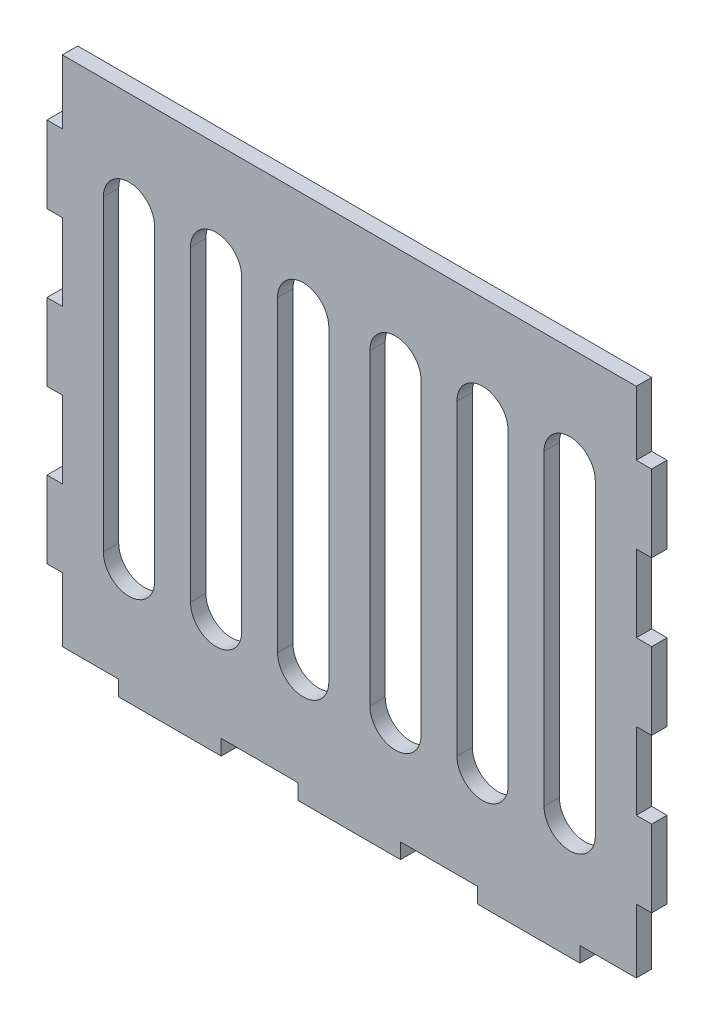
SolidWorks part; units mm, degrees
ref_plane "Front Plane" through (0, 0, 0) normal (0, 0, 1) x (1, 0, 0)
ref_plane "Top Plane" through (0, 0, 0) normal (0, 1, 0) x (1, 0, 0)
ref_plane "Right Plane" through (0, 0, 0) normal (1, 0, 0) x (0, 0, -1)
sketch "Sketch1" plane through (0, 0, 0) normal (0, 0, 1) x (1, 0, 0)
  line L0 (-43, -30) -> (-43, 30) construction
  line L1 (56, -50) -> (-56, -50)
  line L2 (56, -50) -> (56, 50)
  line L3 (56, 50) -> (-56, 50)
  line L4 (-56, -50) -> (-56, 50)
  line L5 (56, -50) -> (-56, 50) construction
  line L6 (56, 50) -> (-56, -50) construction
  line L7 (-48, -30) -> (-48, 30)
  line L8 (-38, -30) -> (-38, 30)
  line L9 (-26, -30) -> (-26, 30) construction
  line L10 (-31, -30) -> (-31, 30)
  line L11 (-21, -30) -> (-21, 30)
  line L12 (-9, -30) -> (-9, 30) construction
  line L13 (-14, -30) -> (-14, 30)
  line L14 (-4, -30) -> (-4, 30)
  line L15 (0, -55) -> (0, 55) construction
  line L16 (9, -30) -> (9, 30) construction
  line L17 (14, -30) -> (14, 30)
  line L18 (4, -30) -> (4, 30)
  line L19 (26, -30) -> (26, 30) construction
  line L20 (31, -30) -> (31, 30)
  line L21 (21, -30) -> (21, 30)
  line L22 (43, -30) -> (43, 30) construction
  line L23 (48, -30) -> (48, 30)
  line L24 (38, -30) -> (38, 30)
  line L25 (-25, -50) -> (-45, -50)
  line L26 (10, -53) -> (-10, -53)
  line L27 (10, -53) -> (10, -50)
  line L28 (10, -50) -> (-10, -50)
  line L29 (-10, -53) -> (-10, -50)
  line L30 (10, -53) -> (-10, -50) construction
  line L31 (10, -50) -> (-10, -53) construction
  line L32 (-59, -7.5) -> (-56, -7.5)
  line L33 (-59, -7.5) -> (-59, 7.5)
  line L34 (-59, 7.5) -> (-56, 7.5)
  line L35 (-56, -7.5) -> (-56, 7.5)
  line L36 (-59, -7.5) -> (-56, 7.5) construction
  line L37 (-59, 7.5) -> (-56, -7.5) construction
  line L38 (-56, 22.5) -> (-59, 22.5)
  line L39 (-56, 22.5) -> (-56, 37.5)
  line L40 (-56, 37.5) -> (-59, 37.5)
  line L41 (-59, 22.5) -> (-59, 37.5)
  line L42 (-56, 22.5) -> (-59, 37.5) construction
  line L43 (-56, 37.5) -> (-59, 22.5) construction
  line L44 (25, -53) -> (45, -53)
  line L45 (25, -53) -> (25, -50)
  line L46 (25, -50) -> (45, -50)
  line L47 (45, -53) -> (45, -50)
  line L48 (25, -53) -> (45, -50) construction
  line L49 (25, -50) -> (45, -53) construction
  line L50 (-45, -53) -> (-45, -50)
  line L51 (-25, -53) -> (-45, -53)
  line L52 (-25, -53) -> (-25, -50)
  line L53 (59, 7.5) -> (56, 7.5)
  line L54 (56, -7.5) -> (56, 7.5)
  line L55 (59, -7.5) -> (56, -7.5)
  line L56 (59, -7.5) -> (59, 7.5)
  line L57 (56, 37.5) -> (59, 37.5)
  line L58 (59, 22.5) -> (59, 37.5)
  line L59 (56, 22.5) -> (59, 22.5)
  line L60 (56, 22.5) -> (56, 37.5)
  line L61 (56, -22.5) -> (59, -22.5)
  line L62 (-56, -37.5) -> (-59, -37.5)
  line L63 (-56, -37.5) -> (-56, -22.5)
  line L64 (-56, -22.5) -> (-59, -22.5)
  line L65 (-59, -37.5) -> (-59, -22.5)
  line L66 (-56, -37.5) -> (-59, -22.5) construction
  line L67 (-56, -22.5) -> (-59, -37.5) construction
  line L68 (59, -37.5) -> (59, -22.5)
  line L69 (56, -37.5) -> (59, -37.5)
  line L70 (56, -37.5) -> (56, -22.5)
  arc A0 (-48, -30) -> (-38, -30) centre (-43, -30) ccw
  arc A1 (-38, 30) -> (-48, 30) centre (-43, 30) ccw
  arc A2 (-31, -30) -> (-21, -30) centre (-26, -30) ccw
  arc A3 (-21, 30) -> (-31, 30) centre (-26, 30) ccw
  arc A4 (-14, -30) -> (-4, -30) centre (-9, -30) ccw
  arc A5 (-4, 30) -> (-14, 30) centre (-9, 30) ccw
  arc A6 (14, -30) -> (4, -30) centre (9, -30) cw
  arc A7 (4, 30) -> (14, 30) centre (9, 30) cw
  arc A8 (31, -30) -> (21, -30) centre (26, -30) cw
  arc A9 (21, 30) -> (31, 30) centre (26, 30) cw
  arc A10 (48, -30) -> (38, -30) centre (43, -30) cw
  arc A11 (38, 30) -> (48, 30) centre (43, 30) cw
  point P0 (0, 0)
  point P8 (-43, 0)
  point P15 (-26, 0)
  point P20 (-9, 0)
  point P27 (-57.5, 0)
  point P33 (9, 0)
  point P40 (26, 0)
  point P47 (43, 0)
  point P52 (0, -51.5)
  point P60 (35, -51.5)
  point P61 (-57.5, 30)
  point P83 (-57.5, -30)
  dimension "D4" = 5
  dimension "D1" = 100
  dimension "D2" = 112
  dimension "D3" = 60
  dimension "D5" = 8
  dimension "D6" = 7
  dimension "D7" = 7
  dimension "D8" = 15
  dimension "D9" = 3
  dimension "D10" = 20
  dimension "D11" = 3
  dimension "D12" = 15
  dimension "D13" = 15
  dimension "D14" = 15
extrude "Boss-Extrude1" add sketch "Sketch1" along normal blind 3 contours L41 L38 L4 L40 | L4 L1 L2 L3 A5 L14 A4 L13 A3 L11 A2 L10 A1 L8 A0 L7 L18 A7 L17 A6 L21 A9 L20 A8 L24 A11 L23 A10 | L34 L33 L32 L4 | L51 L52 L1 L50 | L29 L26 L27 L1 | L44 L47 L1 L45 | L55 L56 L53 L2 | L2 L59 L58 L57 | L63 L62 L65 L64 | L61 L68 L69 L70
